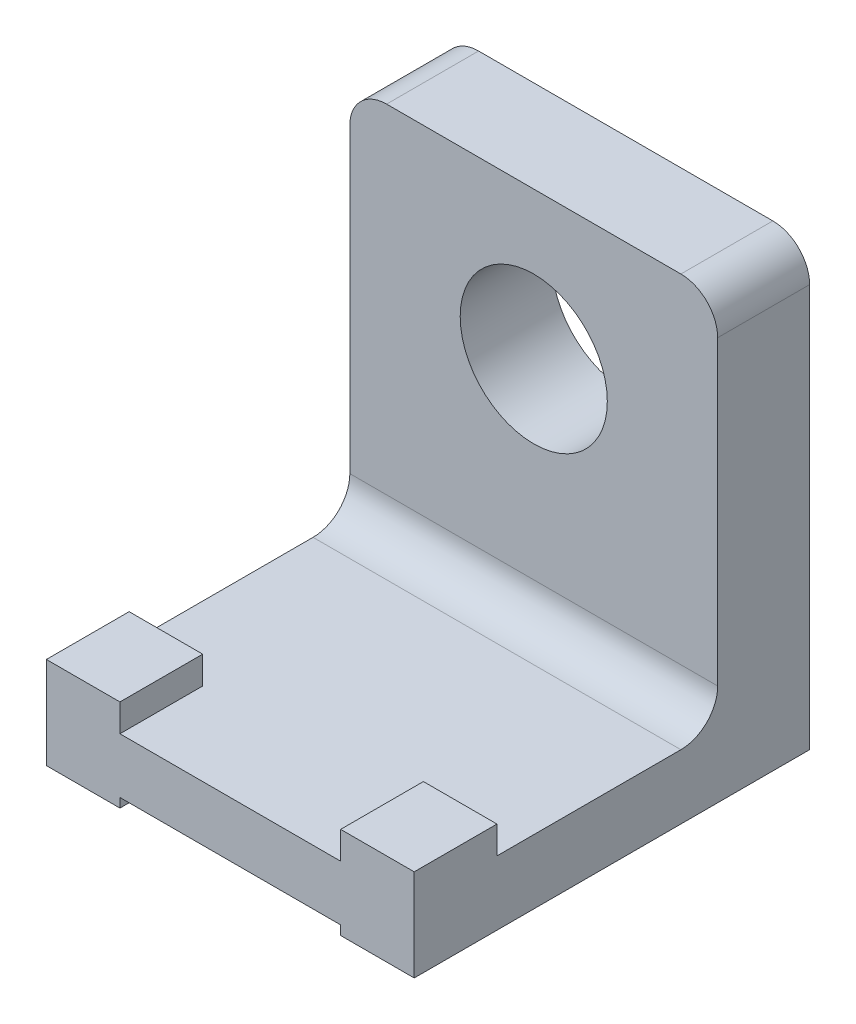
SolidWorks part; units mm, degrees
ref_plane "前视基准面" through (0, 0, 0) normal (0, 0, 1) x (1, 0, 0)
ref_plane "上视基准面" through (0, 0, 0) normal (0, 1, 0) x (1, 0, 0)
ref_plane "右视基准面" through (0, 0, 0) normal (1, 0, 0) x (0, 0, -1)
sketch "草图1" plane through (0, 0, 0) normal (1, 0, 0) x (0, 0, -1)
  line L0 (0, 0) -> (107.95, 0)
  line L1 (107.95, 0) -> (107.95, 75.565)
  line L2 (107.95, 75.565) -> (76.2, 75.565)
  line L3 (76.2, 75.565) -> (76.2, 34.925)
  line L4 (63.5, 22.225) -> (0, 22.225)
  line L5 (0, 22.225) -> (0, 0)
  arc A0 (76.2, 34.925) -> (63.5, 22.225) centre (63.5, 34.925) cw
  dimension "D5" = 12.7
  dimension "D1" = 107.95
  dimension "D2" = 22.225
  dimension "D3" = 75.565
  dimension "D4" = 31.75
extrude "凸台-拉伸2" add sketch "草图1" against normal blind 127 contours L4 L5 L0 L1 L2 L3 A0
sketch "草图2" plane through (0, 0, 0) normal (0, 0, 1) x (1, 0, 0)
  line L0 (0, 0) -> (0, 31.75)
  line L1 (0, 22.225) -> (0, 34.925) construction
  line L2 (0, 31.75) -> (-25.4, 31.75)
  line L3 (-25.4, 31.75) -> (-25.4, 22.225)
  line L4 (-127, 22.225) -> (0, 22.225) construction
  line L5 (-25.4, 22.225) -> (-101.6, 22.225)
  line L10 (-127, 0) -> (0, 0)
  line L11 (-127, 0) -> (-127, 31.75)
  line L12 (-127, 31.75) -> (-101.6, 31.75)
  line L13 (-101.6, 31.75) -> (-101.6, 22.225)
  dimension "D1" = 31.75
  dimension "D2" = 25.4
  dimension "D3" = 76.2
extrude "凸台-拉伸3" add sketch "草图2" along normal blind 28.575
sketch "草图3" plane through (0, 0, -107.95) normal (0, 0, -1) x (-1, 0, 0)
  line L0 (0, 75.565) -> (0, 139.065)
  line L1 (12.7, 151.765) -> (114.3, 151.765)
  line L2 (127, 139.065) -> (127, 75.565)
  line L3 (0, 75.565) -> (127, 75.565)
  arc A0 (114.3, 151.765) -> (127, 139.065) centre (114.3, 139.065) cw
  arc A1 (0, 139.065) -> (12.7, 151.765) centre (12.7, 139.065) cw
  point P11 (0, 151.765)
  point P14 (0, 0)
  point P15 (0, 0)
  dimension "D2" = 12.7
  dimension "D1" = 76.2
extrude "凸台-拉伸6" add sketch "草图3" against normal up to surface (31.75 mm away) contours L1 A0 L2 L3 L0 A1 up to face at (-63.5, 55.245, -76.2)
sketch "草图5" plane through (0, 0, -107.95) normal (0, 0, -1) x (-1, 0, 0)
  line L0 (12.7, 151.765) -> (114.3, 151.765) construction
  line L1 (0, 0) -> (0, 139.065) construction
  circle A0 centre (63.5, 100.965) radius 25.4
  dimension "D1" = 50.8
  dimension "D2" = 50.8
  dimension "D3" = 63.5
extrude "切除-拉伸4" cut sketch "草图5" against normal up to surface (31.75 mm away) up to face at (-63.5, 109.4618, -76.2)
sketch "草图6" plane through (0, 0, 28.575) normal (0, 0, 1) x (1, 0, 0)
  line L0 (-101.6, 0) -> (-101.6, 3.175)
  line L1 (-127, 0) -> (0, 0) construction
  line L2 (-101.6, 3.175) -> (-25.4, 3.175)
  line L3 (-25.4, 3.175) -> (-25.4, 0)
  line L4 (-25.4, 0) -> (-101.6, 0)
  point P8 (-93.8444, -17.5938)
  dimension "D1" = 76.2
  dimension "D2" = 3.175
  dimension "D3" = 25.4
extrude "切除-拉伸5" cut sketch "草图6" against normal up to surface (136.525 mm away) up to face at (-88.9, 100.965, -107.95)
